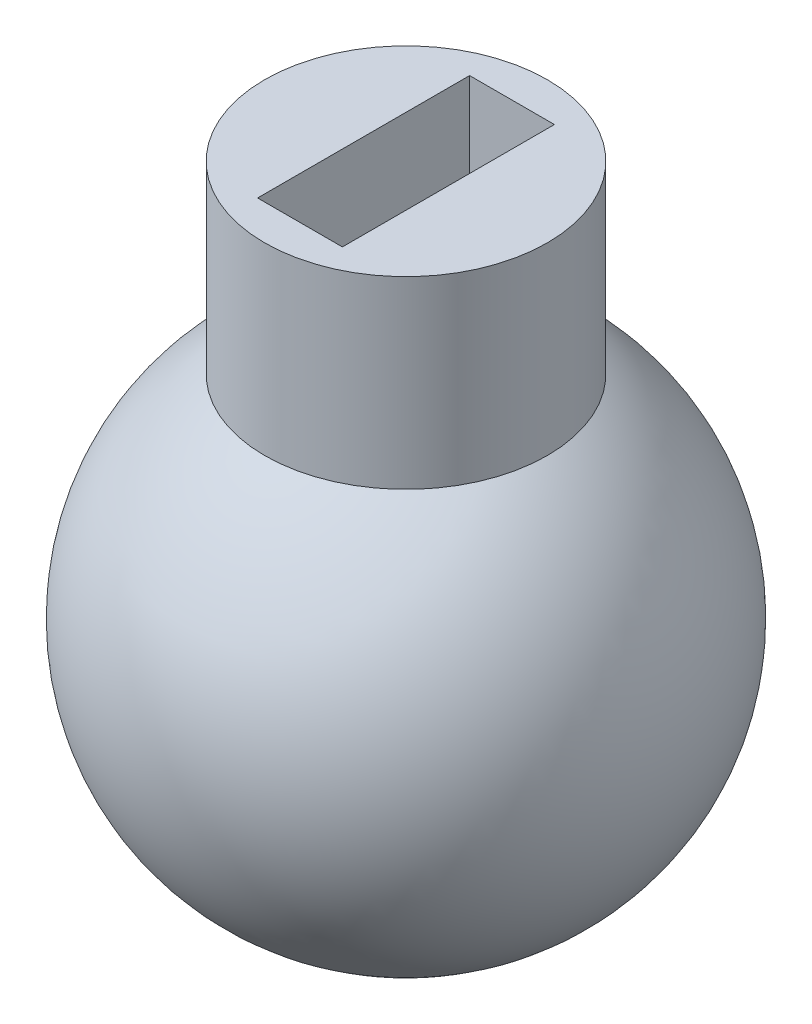
SolidWorks part; units mm, degrees
material "聚亚安酯(11671)"
ref_plane "前视基准面" through (0, 0, 0) normal (0, 0, 1) x (1, 0, 0)
ref_plane "上视基准面" through (0, 0, 0) normal (0, 1, 0) x (1, 0, 0)
ref_plane "右视基准面" through (0, 0, 0) normal (1, 0, 0) x (0, 0, -1)
sketch "草图1" plane through (0, 0, 0) normal (0, 0, 1) x (1, 0, 0)
  line L0 (-95.6313, 0) -> (87.9471, 0) construction
  line L1 (0, 81.2795) -> (0, -79.0569) construction
  line L2 (-10, 28) -> (-10, 14.9666)
  line L3 (-10, 28) -> (0, 28)
  line L5 (0, 28) -> (0, -18)
  arc A0 (-10, 14.9666) -> (0, -18) centre (0, 0) ccw
  dimension "D1" = 18
  dimension "D2" = 28
  dimension "D3" = 10
revolve "旋转1" add sketch "草图1" angle 360 about L1
sketch "草图2" plane through (0, 28, 0) normal (0, 1, 0) x (1, 0, 0)
  line L1 (-3, 7.5) -> (3, 7.5)
  line L2 (-3, 7.5) -> (-3, -7.5)
  line L3 (-3, -7.5) -> (3, -7.5)
  line L4 (3, 7.5) -> (3, -7.5)
  line L5 (-3, 7.5) -> (3, -7.5) construction
  line L6 (-3, -7.5) -> (3, 7.5) construction
  point P0 (0, 0)
  dimension "D1" = 15
  dimension "D2" = 6
extrude "切除-拉伸1" cut sketch "草图2" against normal blind 24
